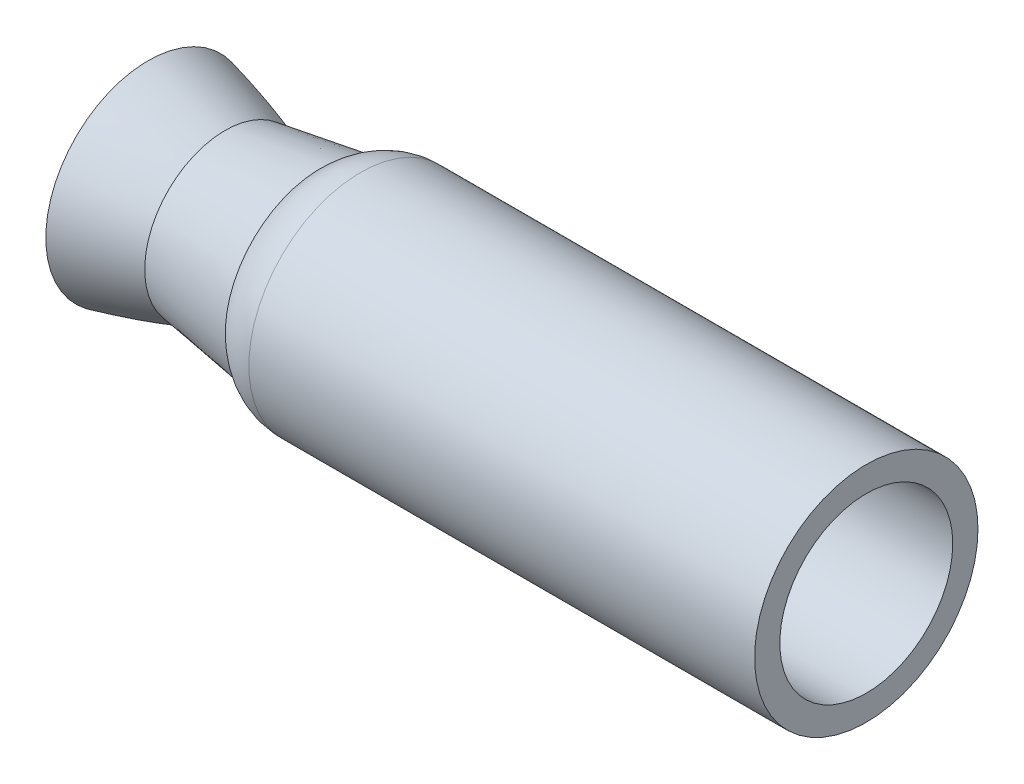
SolidWorks part; units mm, degrees
material "Thornel Mat VMA"
ref_plane "Front Plane" through (0, 0, 0) normal (0, 0, 1) x (1, 0, 0)
ref_plane "Top Plane" through (0, 0, 0) normal (0, 1, 0) x (1, 0, 0)
ref_plane "Right Plane" through (0, 0, 0) normal (1, 0, 0) x (0, 0, -1)
sketch "Sketch1" plane through (0, 0, 0) normal (0, 0, 1) x (1, 0, 0)
  line L0 (189.133, 27.386) -> (28.9492, 27.386)
  line L1 (21.8782, 24.4571) -> (13.5417, 16.1206)
  line L3 (0, 0) -> (-234.9488, 0) construction
  line L5 (16.2213, 30.1139) -> (-13.9816, 25.4377)
  line L6 (-8.3377, 14.8856) -> (19.6623, 22.2412) construction
  line L8 (189.133, 35.386) -> (28.9492, 35.386)
  line L12 (16.2213, 30.1139) -> (7.8848, 21.7775)
  line L13 (189.133, 27.386) -> (189.133, 35.386)
  line L14 (-40.127, 24.64) -> (-38.315, 32.4321)
  line L17 (-8.3377, 14.8856) -> (-11.456, 14.8856) construction
  line L18 (19.6623, 22.2412) -> (22.2041, 23.4265) construction
  line L19 (13.5417, 16.1206) -> (13.5417, 19.4725) construction
  arc A0 (28.9492, 27.386) -> (21.8782, 24.4571) centre (28.9492, 17.386) ccw
  arc A4 (28.9492, 35.386) -> (16.2213, 30.1139) centre (28.9492, 17.386) ccw
  arc A7 (2.3482, 19.2268) -> (2.3482, 19.2268) centre (2.3482, 19.2268) cw
  arc A8 (7.8848, 21.7775) -> (2.3482, 19.2268) centre (1.6623, 28) cw construction
  arc A9 (2.3482, 19.2268) -> (7.8848, 21.7775) centre (1.6623, 28) ccw
  arc A10 (0.1069, 11.2722) -> (0, 11.5361) centre (3.1693, 12.6659) cw construction
  arc A11 (13.5417, 16.1206) -> (0.1069, 11.2722) centre (1.6623, 28) cw construction
  arc A12 (13.5417, 16.1206) -> (1.6623, 11.2) centre (1.6623, 28) cw
  arc A13 (1.6623, 11.2) -> (0, 11.5361) centre (1.6623, 15.4784) cw
  arc A14 (-8.3377, 14.8856) -> (13.5417, 19.4725) centre (-8.3377, 69.3611) ccw
  arc A15 (19.6623, 22.2412) -> (13.5417, 19.4725) centre (-103.6238, 286.629) cw
  spline S0 degree 2 poles (0, 11.5361) (-19.9483, 19.9476) (-40.127, 24.64) knots 0 0 0 1 1 1 construction
  spline S1 degree 1 poles (2.3482, 19.2268) (-38.315, 32.4321) knots 0 0 1 1 construction
  spline S2 degree 2 poles (0, 11.5361) (-19.9483, 19.9476) (-40.127, 24.64) knots 0 0 0 1 1 1
  spline S3 degree 2 poles (2.3482, 19.2268) (0.3135, 20.0775) (-5.8003, 22.5182) (-13.9784, 25.475) (-28.1602, 30.0701) (-38.315, 32.4321) knots 0.018494 0.018494 0.018494 0.117488 0.315475 0.513463 1 1 1
  dimension "D1" = 10
  dimension "D4" = 16.8
  dimension "D5" = 4.2784
  dimension "D14" = 27.386
  dimension "D16" = 167.2548
  dimension "D2" = 11.2
  dimension "D6" = 45
  dimension "D7" = 24.64
  dimension "D8" = 18
  dimension "D9" = 10
  dimension "D10" = 20
  dimension "D3" = 8
revolve "Revolve1" add sketch "Sketch1" angle 360 about L3
equation "\"theta_t\"= 36.9009 - ( 426.271 / ( \"Aet\" + 7.00037 ) ) + ( 10026.8 / ( \"Aet\" + 7.00037 ) ^ 2 ) - ( 175410 / ( \"Aet\" + 7.00037 ) ^ 3 ) + ( ( 1.6742 * ( 10 ^ 6 ) ) / ( \"Aet\" + 7.00037 ) ^ 4 ) - ( ( 6.7643 * ( 10 ^ 6 ) ) / ( \"Aet\" + 7.00037 ) ^ 5 )"
equation "\"rt\"= 11.2"
equation "\"re\"= sqr ( \"rt\" ^ 2 * \"Aet\" )"
equation "\"Aet\"= 4.84"
equation "\"L\"= 0.8 * ( ( \"re\" / tan ( 15 ) ) - ( \"rt\" / tan ( 15 ) ) )"
equation "\"lc\"= ( \"l*\" / \"cr\" )"
equation "\"b\"= tan ( \"theta_t\" )"
equation "\"a\"= ( \"re\" - \"b\" * \"L\" - \"c\" ) / \"L\" ^ 2"
equation "\"c\"= \"rt\" * ( 1.382 - 0.382 * cos ( \"theta_t\" ) )"
equation "\"cr\"= 5.9789"
equation "\"rc\"= sqr ( \"cr\" * ( \"rt\" ^ 2 ) )"
equation "\"D14@Sketch1\"=\"rc\""
equation "\"l*\"= 1000"
equation "\"D16@Sketch1\"=\"lc\""
equation "\"th\"= 8"
equation "\"theta_cr\"= 45deg"
equation "\"theta_e\"= 5.48 + ( 134.316 / ( \"Aet\" + 1.49269 ) ) - ( 1742.02 / ( \"Aet\" + 1.49269 ) ^ 2 ) + ( 13091 / ( \"Aet\" + 1.49269 ) ^ 3 ) - ( 41929.9 / ( \"Aet\" + 1.49269 ) ^ 4 ) + ( 44445.1 / ( \"Aet\" + 1.49269 ) ^ 5 )"
equation "\"Nx\"= 0"
equation "\"Ny\"= \"c\""
equation "\"Qx\"= ( \"re\" - ( tan ( \"theta_e\" ) * \"L\" ) - \"c\" ) / ( tan ( \"theta_t\" ) - tan ( \"theta_e\" ) )"
equation "\"Qy\"= tan ( \"theta_t\" ) * \"Qx\" + \"c\""
equation "\"Ex\"= \"L\""
equation "\"Ey\"= \"re\""
equation "\"D3@Sketch1\"=\"th\""
equation "\"D2@Sketch1\"=\"rt\""
equation "\"D4@Sketch1\"=\"rt\"*1.5"
equation "\"D5@Sketch1\"=\"rt\"*0.382"
equation "\"D6@Sketch1\"=\"theta_cr\""
equation "\"D7@Sketch1\"=\"re\""
